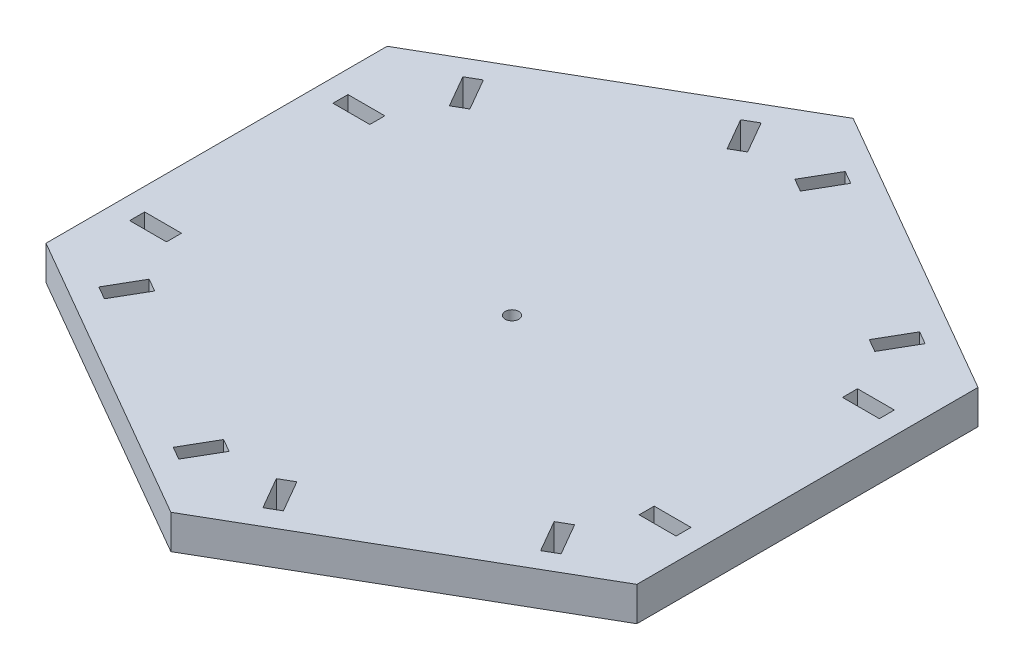
SolidWorks part; units mm, degrees
ref_plane "Front Plane" through (0, 0, 0) normal (0, 0, 1) x (1, 0, 0)
ref_plane "Top Plane" through (0, 0, 0) normal (0, 1, 0) x (1, 0, 0)
ref_plane "Right Plane" through (0, 0, 0) normal (1, 0, 0) x (0, 0, -1)
sketch "Sketch1" plane through (0, 0, 0) normal (0, 1, 0) x (1, 0, 0)
  line L0 (-43.9941, 25.4) -> (0, 0) construction
  line L1 (43.9941, 25.4) -> (0, 50.8)
  line L2 (0, 50.8) -> (-43.9941, 25.4)
  line L3 (-43.9941, 25.4) -> (-43.9941, -25.4)
  line L4 (-43.9941, -25.4) -> (0, -50.8)
  line L5 (0, -50.8) -> (43.9941, -25.4)
  line L6 (43.9941, -25.4) -> (43.9941, 25.4)
  line L7 (-43.0237, 33.8792) -> (-39.5947, 27.94)
  line L8 (-50.8521, 17.526) -> (-43.9941, 17.526)
  line L9 (-50.8521, 17.526) -> (-50.8521, 20.32)
  line L10 (-50.8521, 20.32) -> (-43.9941, 20.32)
  line L11 (-43.9941, 17.526) -> (-43.9941, 20.32)
  line L12 (-50.8521, 17.526) -> (-43.9941, 20.32) construction
  line L13 (-50.8521, 20.32) -> (-43.9941, 17.526) construction
  line L14 (54.9926, 31.75) -> (0, 63.5)
  line L15 (0, 63.5) -> (-54.9926, 31.75)
  line L16 (-54.9926, 31.75) -> (-54.9926, -31.75)
  line L17 (-54.9926, -31.75) -> (0, -63.5)
  line L18 (0, -63.5) -> (54.9926, -31.75)
  line L19 (54.9926, -31.75) -> (54.9926, 31.75)
  line L20 (-37.175, 29.337) -> (-39.5947, 27.94)
  line L21 (-40.604, 35.2762) -> (-37.175, 29.337)
  line L22 (-40.604, 35.2762) -> (-43.0237, 33.8792)
  line L23 (-10.2481, 52.8022) -> (-7.8284, 54.1992)
  line L24 (-10.2481, 52.8022) -> (-6.8191, 46.863)
  line L25 (-6.8191, 46.863) -> (-4.3994, 48.26)
  line L26 (-7.8284, 54.1992) -> (-4.3994, 48.26)
  line L27 (7.8284, 54.1992) -> (4.3994, 48.26)
  line L28 (6.8191, 46.863) -> (4.3994, 48.26)
  line L29 (10.2481, 52.8022) -> (6.8191, 46.863)
  line L30 (10.2481, 52.8022) -> (7.8284, 54.1992)
  line L31 (40.604, 35.2762) -> (43.0237, 33.8792)
  line L32 (40.604, 35.2762) -> (37.175, 29.337)
  line L33 (37.175, 29.337) -> (39.5947, 27.94)
  line L34 (43.0237, 33.8792) -> (39.5947, 27.94)
  line L35 (50.8521, 20.32) -> (43.9941, 20.32)
  line L36 (43.9941, 17.526) -> (43.9941, 20.32)
  line L37 (50.8521, 17.526) -> (43.9941, 17.526)
  line L38 (50.8521, 17.526) -> (50.8521, 20.32)
  line L39 (50.8521, -17.526) -> (50.8521, -20.32)
  line L40 (50.8521, -17.526) -> (43.9941, -17.526)
  line L41 (43.9941, -17.526) -> (43.9941, -20.32)
  line L42 (50.8521, -20.32) -> (43.9941, -20.32)
  line L43 (43.0237, -33.8792) -> (39.5947, -27.94)
  line L44 (37.175, -29.337) -> (39.5947, -27.94)
  line L45 (40.604, -35.2762) -> (37.175, -29.337)
  line L46 (40.604, -35.2762) -> (43.0237, -33.8792)
  line L47 (10.2481, -52.8022) -> (7.8284, -54.1992)
  line L48 (10.2481, -52.8022) -> (6.8191, -46.863)
  line L49 (6.8191, -46.863) -> (4.3994, -48.26)
  line L50 (7.8284, -54.1992) -> (4.3994, -48.26)
  line L51 (-7.8284, -54.1992) -> (-4.3994, -48.26)
  line L52 (-6.8191, -46.863) -> (-4.3994, -48.26)
  line L53 (-10.2481, -52.8022) -> (-6.8191, -46.863)
  line L54 (-10.2481, -52.8022) -> (-7.8284, -54.1992)
  line L55 (-40.604, -35.2762) -> (-43.0237, -33.8792)
  line L56 (-40.604, -35.2762) -> (-37.175, -29.337)
  line L57 (-37.175, -29.337) -> (-39.5947, -27.94)
  line L58 (-43.0237, -33.8792) -> (-39.5947, -27.94)
  line L59 (-50.8521, -20.32) -> (-43.9941, -20.32)
  line L60 (-43.9941, -17.526) -> (-43.9941, -20.32)
  line L61 (-50.8521, -17.526) -> (-43.9941, -17.526)
  line L62 (-50.8521, -17.526) -> (-50.8521, -20.32)
  circle A0 centre (0, 0) radius 43.9941 construction
  circle A1 centre (0, 0) radius 54.9926 construction
  circle A2 centre (0, 0) radius 43.9941 construction
  circle A3 centre (0, 0) radius 43.9941 construction
  circle A4 centre (0, 0) radius 43.9941 construction
  circle A5 centre (0, 0) radius 43.9941 construction
  circle A6 centre (0, 0) radius 43.9941 construction
  circle A7 centre (0, 0) radius 1.27
  point P1 (-47.4231, 18.923)
  point P73 (0, 0)
  dimension "D9" = 2.54
  dimension "D1" = 50.8
  dimension "D2" = 101.6
  dimension "D3" = 2.794
  dimension "D4" = 6.858
  dimension "D5" = 5.08
  dimension "D6" = 3.429
  dimension "D7" = 12.7
  dimension "D8" = 6
extrude "Boss-Extrude1" add sketch "Sketch1" along normal blind 6.35 contours L3 L61 L60 L59 L4 L58 L57 L56 L53 L52 L51 L5 L50 L49 L48 L45 L44 L43 L6 L42 L41 L40 L37 L36 L35 L1 L34 L33 L32 L29 L28 L27 L2 L26 L25 L24 L21 L20 L7 | L18 L19 L14 L15 L16 L17 L6 L5 L4 L3 L2 L1
sketch "Sketch2" plane through (0, 6.35, 0) normal (0, 1, 0) x (1, 0, 0)
  text T0 "PAULINA" font "Century Gothic" height 3.5
